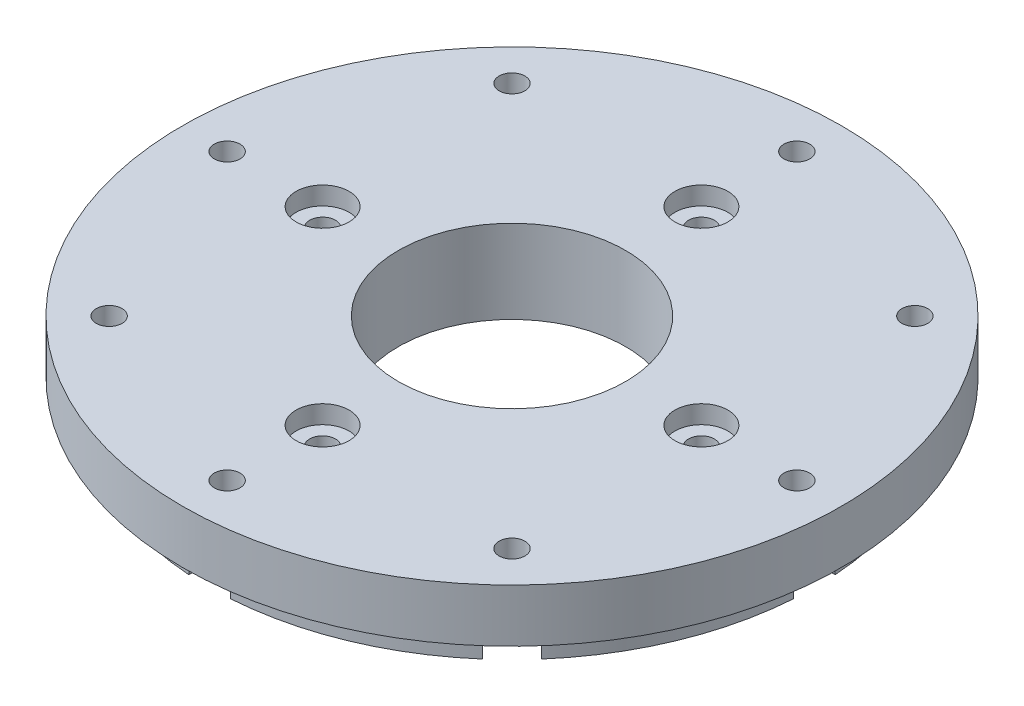
SolidWorks part; units mm, degrees
material "ABS"
ref_plane "Front" through (0, 0, 0) normal (0, 0, 1) x (1, 0, 0)
ref_plane "Top" through (0, 0, 0) normal (0, 1, 0) x (1, 0, 0)
ref_plane "Right" through (0, 0, 0) normal (1, 0, 0) x (0, 0, -1)
sketch "Croquis1" plane through (0, 0, 0) normal (0, 1, 0) x (1, 0, 0)
  circle A0 centre (0, 0) radius 40
  circle A1 centre (0, 0) radius 15
  dimension "D1" = 80
  dimension "D2" = 30
extrude "Saliente-Extruir1" add sketch "Croquis1" along normal mid plane 4
sketch "Croquis2" plane through (0, 2, 0) normal (0, 1, 0) x (1, 0, 0)
  circle A0 centre (0, 0) radius 43.5
  circle A1 centre (0, 0) radius 15
  dimension "D1" = 87
  dimension "D2" = 30
extrude "Saliente-Extruir2" add sketch "Croquis2" along normal blind 7
hole_wizard "Taladro de margen para M31" positions "Croquis3" profile "Croquis4" hole size "M3" standard "Ansi Metric"
sketch "Croquis3" plane through (0, 9, 0) normal (0, 1, 0) x (1, 0, 0)
  line L0 (0, -6.05) -> (0, 6.05) construction
  line L5 (0, 32.7) -> (0, 42.5) construction
  circle A0 centre (0, 0) radius 32.7
  point P0 (0, 37.6)
  point P11 (26.5872, 26.5872)
  point P12 (37.6, 0)
  point P13 (26.5872, -26.5872)
  point P14 (0, -37.6)
  point P15 (-26.5872, -26.5872)
  point P18 (-37.6, 0)
  point P19 (-26.5872, 26.5872)
  point P40 (0, 0)
  dimension "D3" = 65.4
  dimension "D1" = 42.5
  dimension "D2" = 8
sketch "Croquis4" plane through (0, 9, -37.6) normal (1, 0, 0) x (0, 0, 1)
  line L0 (0, 0) -> (0, 21.0215)
  line L1 (0, 21.0215) -> (1.7, 20)
  line L2 (1.7, 20) -> (1.7, 0)
  line L5 (1.7, 0) -> (0, 0)
  line L10 (0, 21.0215) -> (-1.7, 20) construction
  line L11 (0, -6.35) -> (0, 107.95) construction
  dimension "Diámetro de taladro" = 3.4
  dimension "Profundidad de taladro" = 20
  dimension "Ángulo de perforador" = 118
sketch "Croquis5" plane through (0, -2, 0) normal (0, -1, 0) x (1, 0, 0)
  line L1 (0, 40.78) -> (-2.754, 39.19) construction
  line L2 (-2.754, 39.19) -> (-2.754, 36.01)
  line L3 (-2.754, 36.01) -> (0, 34.42)
  line L4 (0, 34.42) -> (2.754, 36.01)
  line L5 (2.754, 36.01) -> (2.754, 39.19)
  line L6 (2.754, 39.19) -> (0, 40.78) construction
  line L51 (0, -6.05) -> (0, 6.05) construction
  line L58 (2.754, 39.19) -> (2.754, 39.9051)
  line L59 (-2.754, 39.19) -> (-2.754, 39.9051)
  line L66 (0, 40.78) -> (-1.393, 39.9757)
  line L74 (0, 40.78) -> (1.393, 39.9757)
  line L82 (25.7642, 29.6589) -> (23.5156, 27.4103)
  line L90 (23.5156, 27.4103) -> (24.3386, 24.3386)
  line L98 (24.3386, 24.3386) -> (27.4103, 23.5156)
  line L106 (27.4103, 23.5156) -> (29.6589, 25.7642)
  line L113 (29.6589, 25.7642) -> (30.1645, 26.2698)
  line L114 (25.7642, 29.6589) -> (26.2698, 30.1645)
  line L115 (28.8358, 28.8358) -> (27.2821, 29.2521)
  line L116 (28.8358, 28.8358) -> (29.2521, 27.2821)
  line L117 (28.8358, 28.8358) -> (25.7642, 29.6589) construction
  line L118 (29.6589, 25.7642) -> (28.8358, 28.8358) construction
  line L119 (39.19, 2.754) -> (36.01, 2.754)
  line L120 (36.01, 2.754) -> (34.42, 0)
  line L121 (34.42, 0) -> (36.01, -2.754)
  line L122 (36.01, -2.754) -> (39.19, -2.754)
  line L123 (39.19, -2.754) -> (39.9051, -2.754)
  line L124 (39.19, 2.754) -> (39.9051, 2.754)
  line L125 (40.78, 0) -> (39.9757, 1.393)
  line L126 (40.78, 0) -> (39.9757, -1.393)
  line L127 (40.78, 0) -> (39.19, 2.754) construction
  line L128 (39.19, -2.754) -> (40.78, 0) construction
  line L129 (29.6589, -25.7642) -> (27.4103, -23.5156)
  line L130 (27.4103, -23.5156) -> (24.3386, -24.3386)
  line L131 (24.3386, -24.3386) -> (23.5156, -27.4103)
  line L132 (23.5156, -27.4103) -> (25.7642, -29.6589)
  line L133 (25.7642, -29.6589) -> (26.2698, -30.1645)
  line L134 (29.6589, -25.7642) -> (30.1645, -26.2698)
  line L135 (28.8358, -28.8358) -> (29.2521, -27.2821)
  line L136 (28.8358, -28.8358) -> (27.2821, -29.2521)
  line L137 (28.8358, -28.8358) -> (29.6589, -25.7642) construction
  line L138 (25.7642, -29.6589) -> (28.8358, -28.8358) construction
  line L139 (2.754, -39.19) -> (2.754, -36.01)
  line L140 (2.754, -36.01) -> (0, -34.42)
  line L141 (0, -34.42) -> (-2.754, -36.01)
  line L142 (-2.754, -36.01) -> (-2.754, -39.19)
  line L143 (-2.754, -39.19) -> (-2.754, -39.9051)
  line L144 (2.754, -39.19) -> (2.754, -39.9051)
  line L145 (0, -40.78) -> (1.393, -39.9757)
  line L146 (0, -40.78) -> (-1.393, -39.9757)
  line L147 (0, -40.78) -> (2.754, -39.19) construction
  line L148 (-2.754, -39.19) -> (0, -40.78) construction
  line L149 (-25.7642, -29.6589) -> (-23.5156, -27.4103)
  line L150 (-23.5156, -27.4103) -> (-24.3386, -24.3386)
  line L151 (-24.3386, -24.3386) -> (-27.4103, -23.5156)
  line L152 (-27.4103, -23.5156) -> (-29.6589, -25.7642)
  line L153 (-29.6589, -25.7642) -> (-30.1645, -26.2698)
  line L154 (-25.7642, -29.6589) -> (-26.2698, -30.1645)
  line L155 (-28.8358, -28.8358) -> (-27.2821, -29.2521)
  line L156 (-28.8358, -28.8358) -> (-29.2521, -27.2821)
  line L157 (-28.8358, -28.8358) -> (-25.7642, -29.6589) construction
  line L158 (-29.6589, -25.7642) -> (-28.8358, -28.8358) construction
  line L159 (-39.19, -2.754) -> (-36.01, -2.754)
  line L160 (-36.01, -2.754) -> (-34.42, 0)
  line L161 (-34.42, 0) -> (-36.01, 2.754)
  line L162 (-36.01, 2.754) -> (-39.19, 2.754)
  line L163 (-39.19, 2.754) -> (-39.9051, 2.754)
  line L164 (-39.19, -2.754) -> (-39.9051, -2.754)
  line L165 (-40.78, 0) -> (-39.9757, -1.393)
  line L166 (-40.78, 0) -> (-39.9757, 1.393)
  line L167 (-40.78, 0) -> (-39.19, -2.754) construction
  line L168 (-39.19, 2.754) -> (-40.78, 0) construction
  line L169 (-29.6589, 25.7642) -> (-27.4103, 23.5156)
  line L170 (-27.4103, 23.5156) -> (-24.3386, 24.3386)
  line L171 (-24.3386, 24.3386) -> (-23.5156, 27.4103)
  line L172 (-23.5156, 27.4103) -> (-25.7642, 29.6589)
  line L173 (-25.7642, 29.6589) -> (-26.2698, 30.1645)
  line L174 (-29.6589, 25.7642) -> (-30.1645, 26.2698)
  line L175 (-28.8358, 28.8358) -> (-29.2521, 27.2821)
  line L176 (-28.8358, 28.8358) -> (-27.2821, 29.2521)
  line L177 (-28.8358, 28.8358) -> (-29.6589, 25.7642) construction
  line L178 (-25.7642, 29.6589) -> (-28.8358, 28.8358) construction
  circle A0 centre (0, 37.6) radius 2.754 construction
  arc A3 (-1.393, 39.9757) -> (-2.754, 39.9051) centre (0, 0) ccw
  circle A7 centre (0, 0) radius 40 construction
  arc A9 (2.754, 39.9051) -> (1.393, 39.9757) centre (0, 0) ccw
  arc A20 (27.2821, 29.2521) -> (26.2698, 30.1645) centre (0, 0) ccw
  arc A21 (30.1645, 26.2698) -> (29.2521, 27.2821) centre (0, 0) ccw
  circle A22 centre (26.5872, 26.5872) radius 2.754 construction
  arc A23 (39.9757, 1.393) -> (39.9051, 2.754) centre (0, 0) ccw
  arc A24 (39.9051, -2.754) -> (39.9757, -1.393) centre (0, 0) ccw
  circle A25 centre (37.6, 0) radius 2.754 construction
  arc A26 (29.2521, -27.2821) -> (30.1645, -26.2698) centre (0, 0) ccw
  arc A27 (26.2698, -30.1645) -> (27.2821, -29.2521) centre (0, 0) ccw
  circle A28 centre (26.5872, -26.5872) radius 2.754 construction
  arc A29 (1.393, -39.9757) -> (2.754, -39.9051) centre (0, 0) ccw
  arc A30 (-2.754, -39.9051) -> (-1.393, -39.9757) centre (0, 0) ccw
  circle A31 centre (0, -37.6) radius 2.754 construction
  arc A32 (-27.2821, -29.2521) -> (-26.2698, -30.1645) centre (0, 0) ccw
  arc A33 (-30.1645, -26.2698) -> (-29.2521, -27.2821) centre (0, 0) ccw
  circle A34 centre (-26.5872, -26.5872) radius 2.754 construction
  arc A35 (-39.9757, -1.393) -> (-39.9051, -2.754) centre (0, 0) ccw
  arc A36 (-39.9051, 2.754) -> (-39.9757, 1.393) centre (0, 0) ccw
  circle A37 centre (-37.6, 0) radius 2.754 construction
  arc A38 (-29.2521, 27.2821) -> (-30.1645, 26.2698) centre (0, 0) ccw
  arc A39 (-26.2698, 30.1645) -> (-27.2821, 29.2521) centre (0, 0) ccw
  circle A40 centre (-26.5872, 26.5872) radius 2.754 construction
  dimension "D1" = 3.18
extrude "Cortar-Extruir1" cut sketch "Croquis5" against normal blind 7
hole_wizard "Refrentado para tornillo con cabeza troncocónica de M32" positions "Croquis6" profile "Croquis8" counterbore size "M3" standard "Ansi Metric"
sketch "Croquis6" plane through (0, 9, 0) normal (0, 1, 0) x (1, 0, 0)
  line L0 (0, -6.05) -> (0, 6.05) construction
  line L1 (-6.05, 0) -> (6.05, 0) construction
  point P0 (0, 25)
  point P11 (25, 0)
  point P12 (0, -25)
  point P13 (-25, 0)
  dimension "D1" = 25
  dimension "D2" = 4
sketch "Croquis8" plane through (0, 9, -25) normal (1, 0, 0) x (0, 0, 1)
  line L0 (0, 0) -> (0, 21.0215)
  line L1 (0, 21.0215) -> (1.7, 20)
  line L2 (1.7, 20) -> (1.7, 2.4)
  line L3 (1.7, 2.4) -> (3.5, 2.4)
  line L4 (3.5, 2.4) -> (3.5, 0)
  line L5 (3.5, 0) -> (0, 0)
  line L10 (0, 21.0215) -> (-1.7, 20) construction
  line L11 (0, -6.35) -> (0, 107.95) construction
  dimension "Diámetro de taladro" = 3.4
  dimension "Profundidad de taladro" = 20
  dimension "Diámetro de refrentado" = 7
  dimension "Profundidad de refrentado" = 2.4
  dimension "Ángulo de perforador" = 118
